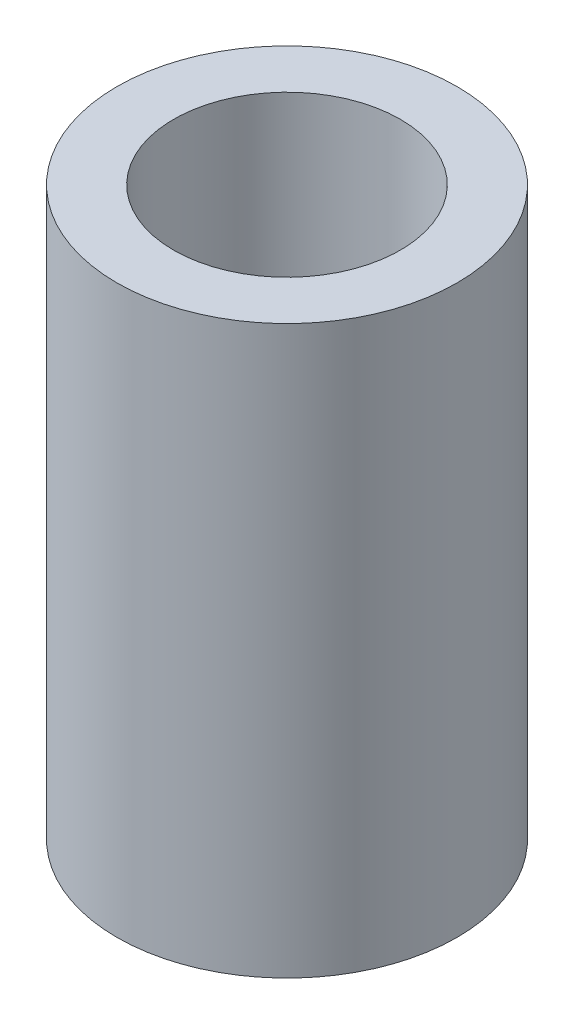
SolidWorks part; units mm, degrees
ref_plane "Front Plane" through (0, 0, 0) normal (0, 0, 1) x (1, 0, 0)
ref_plane "Top Plane" through (0, 0, 0) normal (0, 1, 0) x (1, 0, 0)
ref_plane "Right Plane" through (0, 0, 0) normal (1, 0, 0) x (0, 0, -1)
sketch "Sketch1" plane through (0, 0, 0) normal (0, 1, 0) x (1, 0, 0)
  circle A0 centre (0, 0) radius 4
  circle A1 centre (0, 0) radius 6
  dimension "D1" = 8
  dimension "D2" = 12
extrude "Boss-Extrude1" add sketch "Sketch1" along normal blind 20
